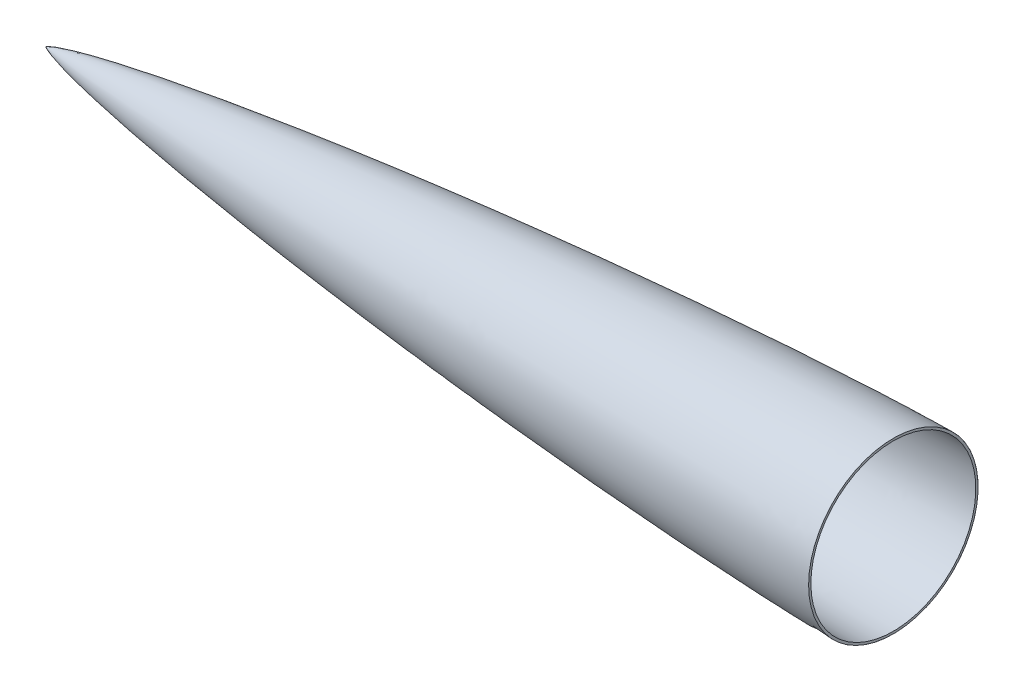
SolidWorks part; units mm, degrees
material "Fibra di Carbonio"
ref_plane "Front Plane" through (0, 0, 0) normal (0, 0, 1) x (1, 0, 0)
ref_plane "Top Plane" through (0, 0, 0) normal (0, 1, 0) x (1, 0, 0)
ref_plane "Right Plane" through (0, 0, 0) normal (1, 0, 0) x (0, 0, -1)
sketch "Sketch2" plane through (0, 0, 0) normal (0, 0, 1) x (1, 0, 0)
  line L0 (0, 0) -> (750, 0) construction
  line L1 (750, 75) -> (750, 0) construction
  line L2 (0, 0) -> (4.5526, 0)
  line L3 (750, 75) -> (750.005, 73)
  line L4 (4.5526, 0) -> (18.241, -6.6941) construction
  line L5 (0, 0) -> (17.3624, -8.4908) construction
  line L6 (750.005, 73) -> (750.005, 75)
  line L7 (750, 75) -> (750.005, 75)
  spline S0 degree 4 poles (0, 0) (0.0027, 0.0074) (0.0091, 0.0215) (0.0269, 0.047) (0.0684, 0.0933) (0.1314, 0.151) (0.2168, 0.2183) (0.3382, 0.3041) (0.4839, 0.3974) (0.6551, 0.4981) (0.8516, 0.6056) (1.1377, 0.7534) (1.5815, 0.9661) (2.3351, 1.2961) (3.6829, 1.8266) (6.1115, 2.6745) (10.5746, 4.038) (18.9517, 6.252) (33.5701, 9.5653) (58.4067, 14.4079) (92.5079, 20.1209) (133.842, 26.2251) (179.8092, 32.3065) (225.8421, 37.8632) (271.9254, 42.9839) (318.0491, 47.7253) (364.2071, 52.1207) (410.3947, 56.191) (456.6091, 59.9459) (502.848, 63.3865) (549.1098, 66.5042) (595.3934, 69.2798) (635.9102, 71.3773) (670.652, 72.8985) (698.6683, 73.9066) (717.5285, 74.458) (733.0226, 74.8041) (742.7236, 74.948) (747.5745, 74.994) (750, 75) knots 0 0 0 0 0 0.000041 0.000082 0.000164 0.000329 0.000493 0.000658 0.000951 0.001245 0.001545 0.001844 0.002657 0.003853 0.005902 0.009516 0.016281 0.028569 0.051794 0.088907 0.150314 0.211721 0.273128 0.334535 0.395942 0.457348 0.518755 0.580162 0.641569 0.702976 0.764383 0.825789 0.887196 0.9179 0.948603 0.974302 0.987151 1 1 1 1 1 construction
  spline S1 degree 4 poles (0, 0) (0.0027, 0.0074) (0.0091, 0.0215) (0.0269, 0.047) (0.0684, 0.0933) (0.1314, 0.151) (0.2168, 0.2183) (0.3382, 0.3041) (0.4839, 0.3974) (0.6551, 0.4981) (0.8516, 0.6056) (1.1377, 0.7534) (1.5815, 0.9661) (2.3351, 1.2961) (3.6829, 1.8266) (6.1115, 2.6745) (10.5746, 4.038) (18.9517, 6.252) (33.5701, 9.5653) (58.4067, 14.4079) (92.5079, 20.1209) (133.842, 26.2251) (179.8092, 32.3065) (225.8421, 37.8632) (271.9254, 42.9839) (318.0491, 47.7253) (364.2071, 52.1207) (410.3947, 56.191) (456.6091, 59.9459) (502.848, 63.3865) (549.1098, 66.5042) (595.3934, 69.2798) (635.9102, 71.3773) (670.652, 72.8985) (698.6683, 73.9066) (717.5285, 74.458) (733.0226, 74.8041) (742.7236, 74.948) (747.5745, 74.994) (750, 75) knots 0 0 0 0 0 0.000041 0.000082 0.000164 0.000329 0.000493 0.000658 0.000951 0.001245 0.001545 0.001844 0.002657 0.003853 0.005902 0.009516 0.016281 0.028569 0.051794 0.088907 0.150314 0.211721 0.273128 0.334535 0.395942 0.457348 0.518755 0.580162 0.641569 0.702976 0.764383 0.825789 0.887196 0.9179 0.948603 0.974302 0.987151 1 1 1 1 1
  spline S2 degree 1 poles (4.5526, 0) (750.005, 73) knots 0 0 1 1 construction
  spline S3 degree 3 poles (4.5526, 0) (5.445, 0.3249) (7.239, 0.923) (10.9289, 2.0351) (17.4708, 3.796) (26.9445, 6.0175) (38.3871, 8.4241) (53.7067, 11.3983) (72.9318, 14.7925) (96.0679, 18.5265) (119.2498, 22.0067) (150.2024, 26.3764) (188.9573, 31.415) (235.5315, 36.9454) (282.158, 42.0423) (328.826, 46.7595) (391.0967, 52.5838) (469.0103, 59.0427) (547.0044, 64.4339) (609.4413, 68.0319) (656.2876, 70.325) (695.3421, 71.8297) (722.6802, 72.5863) (738.3058, 72.8883) (746.1038, 72.9903) (750.005, 73) knots 0.005737 0.005737 0.005737 0.005737 0.00962 0.013504 0.021272 0.036807 0.052343 0.067878 0.098949 0.130019 0.16109 0.192161 0.254302 0.316444 0.378585 0.440727 0.502868 0.627151 0.751434 0.813576 0.875717 0.937859 0.968929 0.984465 1 1 1 1
  dimension "D1" = 75
  dimension "D2" = 750
  dimension "D3" = 2
revolve "Revolve1" add sketch "Sketch2" angle 360 about L0
